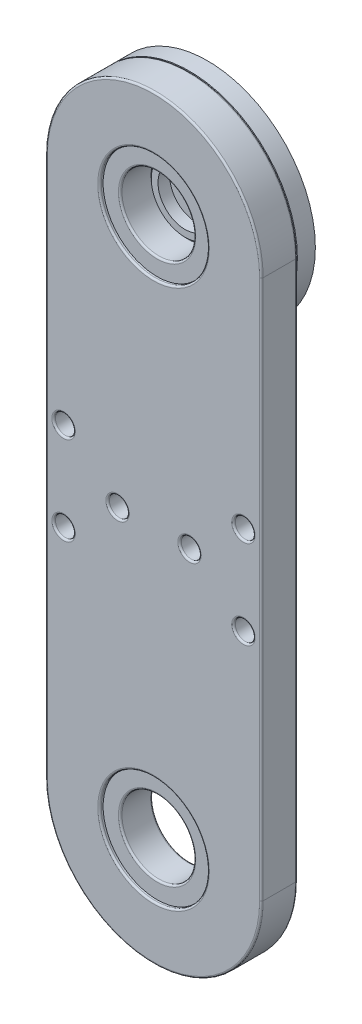
SolidWorks part; units mm, degrees
material "Полибутадиен (PB)"
ref_plane "Спереди" through (0, 0, 0) normal (0, 0, 1) x (1, 0, 0)
ref_plane "Сверху" through (0, 0, 0) normal (0, 1, 0) x (1, 0, 0)
ref_plane "Справа" through (0, 0, 0) normal (1, 0, 0) x (0, 0, -1)
sketch "Эскиз1" plane through (0, 0, 0) normal (1, 0, 0) x (0, 0, -1)
  line L0 (0, 3.75) -> (0, 12)
  line L1 (0, 12) -> (2, 12)
  line L2 (2, 12) -> (2, 4.5)
  line L3 (2, 4.5) -> (4.5, 4.5)
  line L4 (4.5, 4.5) -> (4.5, 3)
  line L5 (4.5, 3) -> (1.5, 3)
  line L6 (-0.5, 3.75) -> (0, 3.75)
  line L7 (-0.5, 3.75) -> (-0.5, 3)
  line L8 (-0.5, 3) -> (0.8, 3)
  line L9 (0.8, 3) -> (0.8, 1.4)
  line L10 (0.8, 1.4) -> (1.5, 1.4)
  line L11 (1.5, 3) -> (1.5, 1.4)
  dimension "D1" = 2
  dimension "D2" = 3
  dimension "D3" = 12
  dimension "D4" = 4.5
  dimension "D5" = 3
  dimension "D6" = 3.75
  dimension "D7" = 3
  dimension "D8" = 0.5
  dimension "D9" = 4.5
  dimension "D10" = 1.3
  dimension "D11" = 1.4
ref_axis "Ось1" through (0, 0, 50) along (0, 0, -1)
revolve "Повернуть1" add sketch "Эскиз1" angle 360 about axis through (0, 0, 50) along (0, 0, -1)
sketch "Эскиз2" plane through (0, 0, 0) normal (0, 0, 1) x (1, 0, 0)
  line L0 (0, 0) -> (8.25, 0) construction
  line L1 (0, 0) -> (7.7525, -2.8217) construction
  line L2 (0, 0) -> (0, 7) construction
  line L3 (0, 0) -> (2.3941, 6.5778) construction
  line L4 (0, 0) -> (0, 7) construction
  line L5 (0, 0) -> (-2.3941, 6.5778) construction
  circle A0 centre (8.25, 0) radius 0.75
  circle A1 centre (7.7525, -2.8217) radius 0.75
  circle A2 centre (7.7525, 2.8217) radius 0.75
  circle A3 centre (-8.25, 0) radius 0.75
  circle A4 centre (-7.7525, -2.8217) radius 0.75
  circle A5 centre (-7.7525, 2.8217) radius 0.75
  circle A6 centre (0, 7) radius 0.75
  circle A8 centre (0, 10) radius 0.75
  circle A9 centre (2.3941, 6.5778) radius 0.75
  circle A10 centre (3.4202, 9.3969) radius 0.75
  circle A11 centre (-2.3941, 6.5778) radius 0.75
  circle A12 centre (-3.4202, 9.3969) radius 0.75
  circle A13 centre (0, -7) radius 0.75
  circle A14 centre (0, -10) radius 0.75
  circle A15 centre (3.4202, -9.3969) radius 0.75
  circle A16 centre (2.3941, -6.5778) radius 0.75
  circle A17 centre (-2.3941, -6.5778) radius 0.75
  circle A18 centre (-3.4202, -9.3969) radius 0.75
  point P12 (0, 0)
  point P20 (0, 0)
  point P51 (0, 0)
  dimension "D1" = 1.5
  dimension "D7" = 1.5
  dimension "D9" = 1.5
  dimension "D2" = 8.25
  dimension "D4" = 20
  dimension "D8" = 7
  dimension "D10" = 10
  dimension "D12" = 20
  dimension "D14" = 20
  dimension "D3" = 2
  dimension "D5" = 2
  dimension "D6" = 2
  dimension "D11" = 2
  dimension "D13" = 2
  dimension "D15" = 2
extrude "Вырез-Вытянуть1" cut sketch "Эскиз2" against normal through all
sketch "스케치1" plane through (0, 0, 0) normal (0, 0, 1) x (1, 0, 0)
  line L0 (-12, 0) -> (-12, -60)
  line L1 (-12, -30) -> (12, -30) construction
  line L2 (12, -60) -> (12, 0)
  circle A0 centre (0, 0) radius 4.1
  circle A1 centre (0, 0) radius 12
  arc A2 (12, 0) -> (-12, 0) centre (0, 0) ccw
  arc A15 (12, -60) -> (-12, -60) centre (0, -60) cw
  circle A16 centre (0, -60) radius 4.1
  circle M7 centre (3.4202, -9.3969) radius 0.75
  circle M8 centre (2.3941, -6.5778) radius 0.75
  circle M9 centre (-3.4202, -9.3969) radius 0.75
  circle M10 centre (-2.3941, -6.5778) radius 0.75
  circle M11 centre (0, -10) radius 0.75
  circle M12 centre (0, -7) radius 0.75
  circle M13 centre (-3.4202, 9.3969) radius 0.75
  circle M14 centre (-2.3941, 6.5778) radius 0.75
  circle M15 centre (3.4202, 9.3969) radius 0.75
  circle M16 centre (2.3941, 6.5778) radius 0.75
  circle M17 centre (0, 10) radius 0.75
  circle M18 centre (-7.7525, -2.8217) radius 0.75
  circle M19 centre (-7.7525, 2.8217) radius 0.75
  circle M20 centre (-8.25, 0) radius 0.75
  circle M21 centre (7.7525, 2.8217) radius 0.75
  circle M22 centre (0, 7) radius 0.75
  circle M23 centre (7.7525, -2.8217) radius 0.75
  circle M24 centre (8.25, 0) radius 0.75
  circle M25 centre (0, 0) radius 12
  dimension "D3" = 8.2
  dimension "D2" = 30
  dimension "D1" = 0
extrude "보스-돌출1" add sketch "스케치1" along normal blind 4 separate body contours L1 L0 A15 L2 A16 | L0 L1 L2 M25 | A0 M25 M8 M10 M12 M14 M16 M18 M20 M22 M24 M23 M21 M19 M17 M15 M13 M11 M9 M7 | M8 | M12 | M10 | M9 | M11 | M7 | M23 | M24 | M21 | M16 | M22 | M14 | M19 | M20 | M18 | M13 | M17 | M15
sketch "스케치2" plane through (0, 0, 0) normal (0, 0, -1) x (-1, 0, 0)
  line L1 (-12, -30) -> (40.626, -30) construction
  line L2 (-12, -60) -> (-12, 0) construction
  line L3 (0, 0) -> (0, -60) construction
  line L5 (12, -60) -> (12, 0)
  line L6 (-12, 0) -> (-12, -60)
  line L7 (12, -34.9201) -> (12, -25.0799)
  line L8 (-12, -25.0799) -> (-12, -34.9201)
  arc A0 (9.2593, -36.7779) -> (-9.2593, -36.7779) centre (0, -60) ccw
  arc A1 (-9.2593, -23.2221) -> (9.2593, -23.2221) centre (0, 0) ccw
  arc A2 (9.2593, -36.7779) -> (12, -34.9201) centre (10, -34.9201) ccw
  arc A3 (-9.2593, -36.7779) -> (-12, -34.9201) centre (-10, -34.9201) cw
  arc A4 (-12, -60) -> (12, -60) centre (0, -60) ccw
  arc A8 (9.2593, -23.2221) -> (12, -25.0799) centre (10, -25.0799) cw
  arc A9 (-9.2593, -23.2221) -> (-12, -25.0799) centre (-10, -25.0799) ccw
  circle A10 centre (-10, -25.0799) radius 0.95
  circle A11 centre (-10, -34.9201) radius 0.95
  circle A12 centre (10, -25.0799) radius 0.95
  circle A13 centre (10, -34.9201) radius 0.95
  circle A15 centre (-4, -30) radius 0.95
  circle A16 centre (4, -30) radius 0.95
  circle A17 centre (-10, -25.0799) radius 1.1
  circle A18 centre (-4, -30) radius 1.1
  circle A19 centre (4, -30) radius 1.1
  circle A20 centre (10, -25.0799) radius 1.1
  circle A21 centre (10, -34.9201) radius 1.1
  circle A22 centre (-10, -34.9201) radius 1.1
  arc A24 (12, 0) -> (-12, 0) centre (0, 0) ccw
  dimension "D1" = 50
  dimension "D3" = 2
  dimension "D4" = 1.9
  dimension "D5" = 8
  dimension "D6" = 2.2
  dimension "D2" = 0
extrude "컷-돌출1" cut sketch "스케치2" against normal through all contours A10 | A17 A10 | A11 | A22 A11 | A15 | A18 A15 | A16 | A19 A16 | A12 | A20 A12 | A13 | A21 A13 | A1 A8 L7 A2 A0 A3 L8 A9
sketch "스케치3" plane through (0, 0, 4) normal (0, 0, 1) x (1, 0, 0)
  circle A0 centre (0, 0) radius 6
  circle A1 centre (0, -60) radius 6
  dimension "D1" = 12
extrude "컷-돌출2" cut sketch "스케치3" against normal blind 0.4
fillet "필렛1" radius 0.2 26 edges at (4.1, -60, 3.6) (4.1, 0, 0) (4.1, -60, 0) (0, 12, 0) (-12, -30, 0) (0, -72, 0) (12, -30, 0) (8.9, -25.0799, 0) (-11.1, -34.9201, 0) (-11.1, -25.0799, 0) (-5.1, -30, 0) (2.9, -30, 0) (8.9, -34.9201, 0) (0, -72, 4) (-12, -30, 4) (0, 12, 4) (12, -30, 4) (8.9, -25.0799, 4) (-11.1, -34.9201, 4) (-11.1, -25.0799, 4) (-5.1, -30, 4) (2.9, -30, 4) (8.9, -34.9201, 4) (6, -60, 4) (6, 0, 4) (4.1, 0, 3.6)
